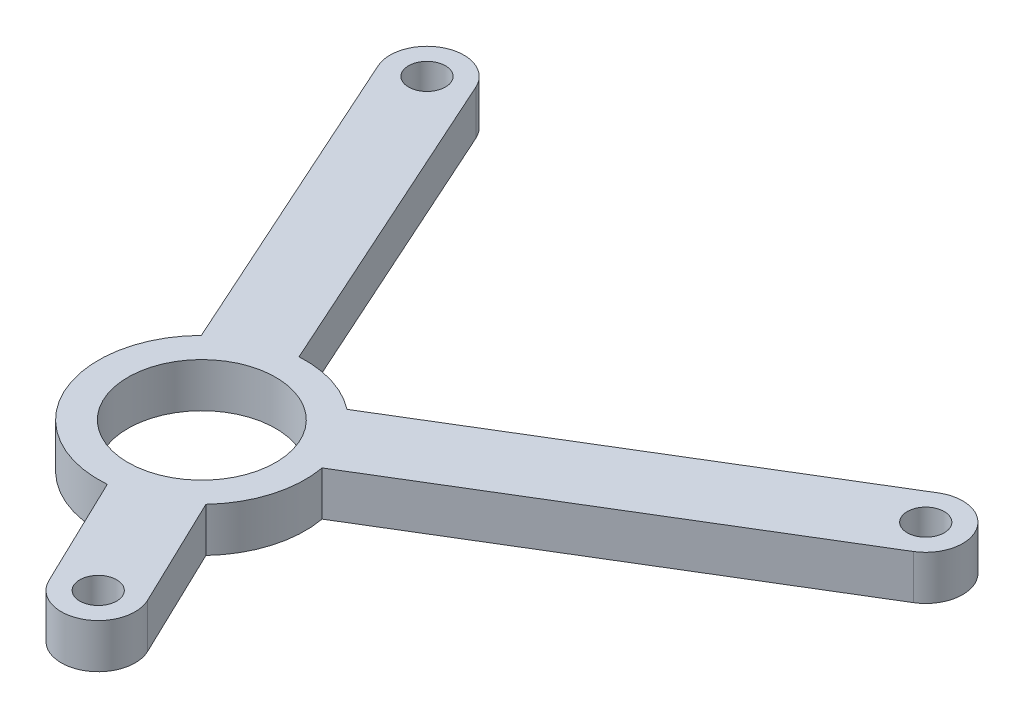
SolidWorks part; units mm, degrees
material "Acrylic (Medium-high impact)"
ref_plane "Front Plane" through (0, 0, 0) normal (0, 0, 1) x (1, 0, 0)
ref_plane "Top Plane" through (0, 0, 0) normal (0, 1, 0) x (1, 0, 0)
ref_plane "Right Plane" through (0, 0, 0) normal (1, 0, 0) x (0, 0, -1)
sketch "Sketch1" plane through (0, 0, 0) normal (0, 1, 0) x (1, 0, 0)
  circle A0 centre (0, 0) radius 27.5
  dimension "D1" = 55
extrude "Boss-Extrude1" add sketch "Sketch1" along normal blind 3
sketch "Sketch2" plane through (0, 3, 0) normal (0, 1, 0) x (1, 0, 0)
  circle A0 centre (0, -25) radius 1.25
  circle A1 centre (0, 0) radius 27.5 construction
  circle A2 centre (24, 7) radius 1.25
  circle A3 centre (-19, 16.2481) radius 1.25
  dimension "D1" = 2.5
  dimension "D2" = 25
  dimension "D3" = 25
  dimension "D4" = 7
  dimension "D5" = 2.5
  dimension "D6" = 25
  dimension "D7" = 19
  dimension "D8" = 2.5
extrude "Cut-Extrude1" cut sketch "Sketch2" against normal blind 3
sketch "Sketch3" plane through (0, 3, 0) normal (0, 1, 0) x (1, 0, 0)
  line L0 (0, -25) -> (-6.49, -11.5) construction
  line L1 (-6.49, -11.5) -> (-19, 16.2481) construction
  line L2 (24, 7) -> (-6.49, -11.5) construction
  line L3 (26.4085, 3.0305) -> (24, 7) construction
  line L4 (24, 7) -> (21.6608, 10.8553) construction
  line L5 (3.5178, -23.3088) -> (0, -25) construction
  line L6 (0, -25) -> (-4.2423, -27.0395) construction
  line L7 (-14.2098, 18.4077) -> (-19, 16.2481) construction
  line L8 (-19, 16.2481) -> (-23.7945, 14.0865) construction
  line L9 (25.2968, 4.8627) -> (0.3967, -10.2457)
  line L10 (22.7032, 9.1373) -> (-2.197, -5.971)
  line L11 (2.2532, -23.9168) -> (-1.404, -16.3096)
  line L12 (-2.2532, -26.0832) -> (-5.9103, -18.476)
  line L13 (-6.8982, -4.5119) -> (-16.7209, 17.2756)
  line L14 (-21.2791, 15.2206) -> (-11.4564, -6.5669)
  circle A0 centre (-6.49, -11.5) radius 5
  circle A1 centre (-6.49, -11.5) radius 7
  circle A2 centre (24, 7) radius 2.5
  circle A3 centre (-19, 16.2481) radius 2.5
  circle A4 centre (0, -25) radius 2.5
  circle A5 centre (0, 0) radius 27.5
  point P18 (0.3967, -10.2457)
  point P20 (-1.404, -16.3096)
  point P23 (-5.9103, -18.476)
  point P24 (-6.8982, -4.5119)
  point P25 (-11.4564, -6.5669)
  circle M8 centre (24, 7) radius 1.25
  circle M9 centre (-19, 16.2481) radius 1.25
  circle M10 centre (0, -25) radius 1.25
  circle M11 centre (0, 0) radius 27.5
  dimension "D5" = 5
  dimension "D7" = 5
  dimension "D11" = 2.5
  dimension "D8" = 90
  dimension "D9" = 90
  dimension "D10" = 90
  dimension "D12" = 2.5
  dimension "D13" = 2.5
  dimension "D14" = 2.5
  dimension "D15" = 2.5
extrude "Cut-Extrude5" cut sketch "Sketch3" against normal blind 3 contours A3 L13 A1 L10 A2 M11 | A4 A2 L9 A1 L11 M11 | A0 | M10 | M8 | M9 | A4 L12 A1 L14 A3 M11
